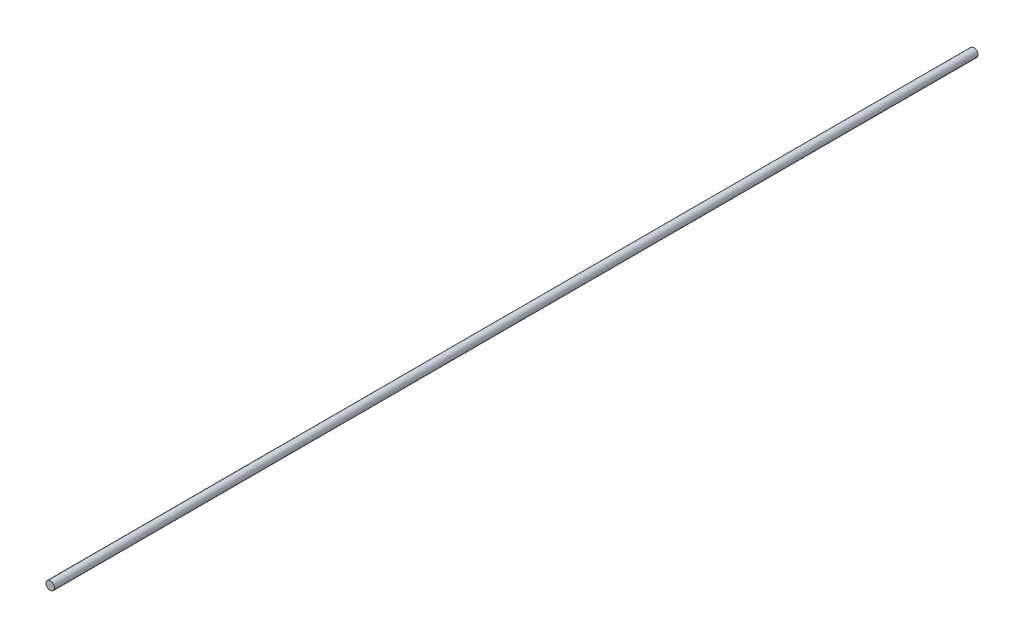
SolidWorks part; units mm, degrees
material "Hexcel AS4C (3000 Filaments)"
ref_plane "Front Plane" through (0, 0, 0) normal (0, 0, 1) x (1, 0, 0)
ref_plane "Top Plane" through (0, 0, 0) normal (0, 1, 0) x (1, 0, 0)
ref_plane "Right Plane" through (0, 0, 0) normal (1, 0, 0) x (0, 0, -1)
sketch "Sketch1" plane through (0, 0, 0) normal (0, 0, 1) x (1, 0, 0)
  circle A0 centre (0, 0) radius 1
  dimension "D1" = 2
extrude "Boss-Extrude1" add sketch "Sketch1" along normal blind 220
